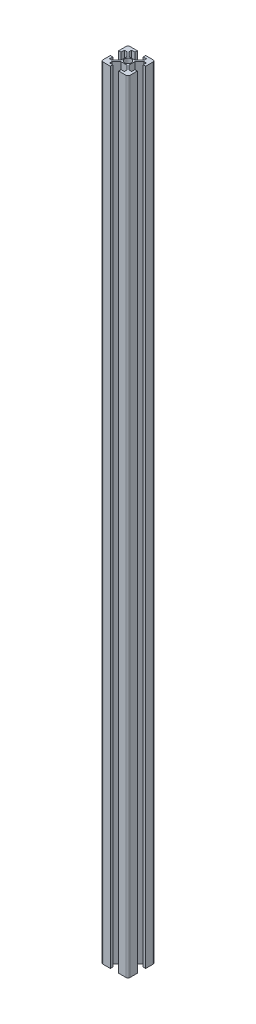
SolidWorks part; units mm, degrees
ref_plane "前视基准面" through (0, 0, 0) normal (0, 0, 1) x (1, 0, 0)
ref_plane "上视基准面" through (0, 0, 0) normal (0, 1, 0) x (1, 0, 0)
ref_plane "右视基准面" through (0, 0, 0) normal (1, 0, 0) x (0, 0, -1)
sketch "草图1" plane through (0, 0, 0) normal (0, 1, 0) x (1, 0, 0)
  line L0 (-29.3048, -8.743) -> (-27.5048, -8.743)
  line L1 (-27.8048, 4.357) -> (-10.8048, 4.357)
  line L2 (-29.3048, 2.857) -> (-29.3048, -14.143)
  line L3 (-27.8048, -15.643) -> (-10.8048, -15.643)
  line L4 (-9.3048, 2.857) -> (-9.3048, -14.143)
  line L5 (-29.3048, 4.357) -> (-9.3048, -15.643) construction
  line L6 (-29.3048, -15.643) -> (-9.3048, 4.357) construction
  line L7 (-22.359, -2.543) -> (-16.2507, -2.543)
  line L8 (-22.359, -2.543) -> (-22.359, -8.743)
  line L9 (-22.359, -8.743) -> (-16.2507, -8.743)
  line L10 (-16.2507, -2.543) -> (-16.2507, -8.743)
  line L11 (-22.359, -2.543) -> (-16.2507, -8.743) construction
  line L12 (-22.359, -8.743) -> (-16.2507, -2.543) construction
  line L13 (-27.5048, -8.743) -> (-27.5048, -11.143)
  line L14 (-27.5048, -11.143) -> (-25.7019, -11.143)
  line L15 (-25.7019, -11.143) -> (-22.359, -7.8)
  line L16 (-24.8048, 0.7541) -> (-21.4619, -2.5888)
  line L17 (-24.8048, 2.557) -> (-24.8048, 0.7541)
  line L18 (-22.4048, 2.557) -> (-24.8048, 2.557)
  line L19 (-22.4048, 4.357) -> (-22.4048, 2.557)
  line L20 (-12.9078, -0.143) -> (-16.2507, -3.4859)
  line L21 (-11.1048, -0.143) -> (-12.9078, -0.143)
  line L22 (-11.1048, -2.543) -> (-11.1048, -0.143)
  line L23 (-9.3048, -2.543) -> (-11.1048, -2.543)
  line L24 (-13.8048, -12.04) -> (-17.1478, -8.6971)
  line L25 (-13.8048, -13.843) -> (-13.8048, -12.04)
  line L26 (-16.2048, -13.843) -> (-13.8048, -13.843)
  line L27 (-16.2048, -15.643) -> (-16.2048, -13.843)
  line L28 (-22.4048, -15.643) -> (-22.4048, -13.843)
  line L29 (-22.4048, -13.843) -> (-24.8048, -13.843)
  line L30 (-24.8048, -13.843) -> (-24.8048, -12.04)
  line L31 (-24.8048, -12.04) -> (-21.4619, -8.6971)
  line L32 (-27.5048, -0.143) -> (-25.7019, -0.143)
  line L33 (-25.7019, -0.143) -> (-22.359, -3.4859)
  line L34 (-27.5048, -2.543) -> (-27.5048, -0.143)
  line L35 (-29.3048, -2.543) -> (-27.5048, -2.543)
  line L36 (-13.8048, 2.557) -> (-13.8048, 0.7541)
  line L37 (-13.8048, 0.7541) -> (-17.1478, -2.5888)
  line L38 (-16.2048, 2.557) -> (-13.8048, 2.557)
  line L39 (-16.2048, 4.357) -> (-16.2048, 2.557)
  line L40 (-11.1048, -11.143) -> (-12.9078, -11.143)
  line L41 (-12.9078, -11.143) -> (-16.2507, -7.8)
  line L42 (-11.1048, -8.743) -> (-11.1048, -11.143)
  line L43 (-9.3048, -8.743) -> (-11.1048, -8.743)
  circle A0 centre (-19.3048, -5.643) radius 2.5
  arc A1 (-29.3048, 2.857) -> (-27.8048, 4.357) centre (-27.8048, 2.857) cw
  arc A2 (-29.3048, -14.143) -> (-27.8048, -15.643) centre (-27.8048, -14.143) ccw
  arc A3 (-10.8048, 4.357) -> (-9.3048, 2.857) centre (-10.8048, 2.857) cw
  arc A4 (-9.3048, -14.143) -> (-10.8048, -15.643) centre (-10.8048, -14.143) cw
  point P0 (-19.3048, -5.643)
  point P19 (-19.3048, -5.643)
  point P25 (-19.3048, -5.643)
  point P31 (-19.3048, -5.643)
  point P37 (-19.3048, -5.643)
  point P59 (-19.3048, -5.643)
extrude "凸台-拉伸1" add sketch "草图1" along normal blind 580
